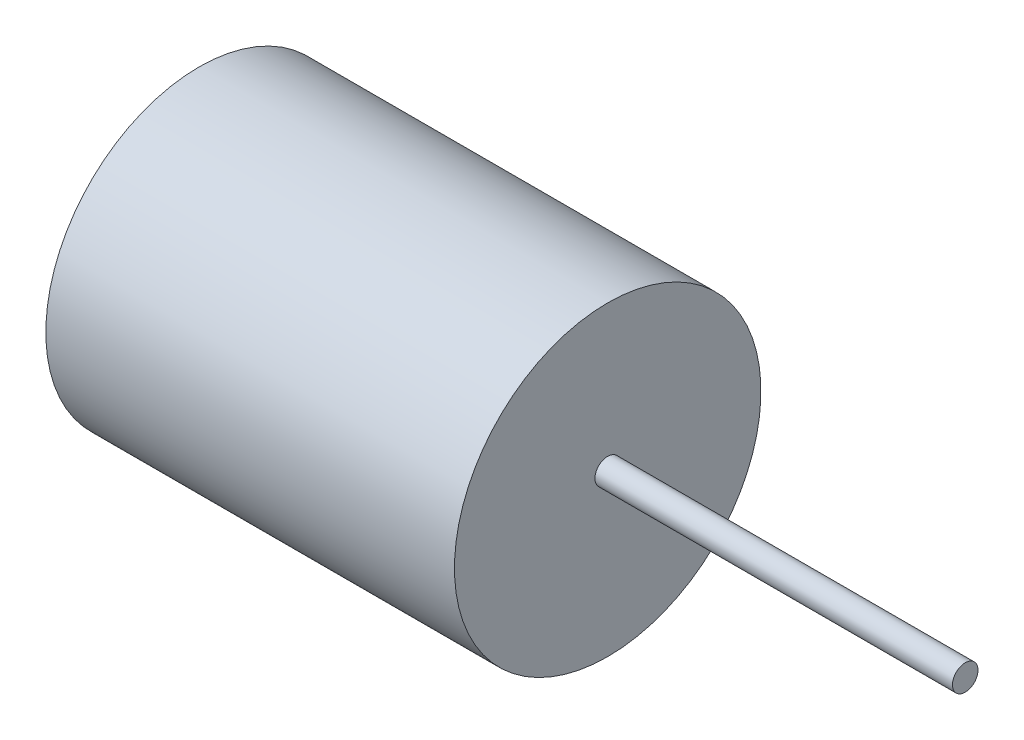
SolidWorks part; units mm, degrees
ref_plane "Front Plane" through (0, 0, 0) normal (0, 0, 1) x (1, 0, 0)
ref_plane "Top Plane" through (0, 0, 0) normal (0, 1, 0) x (1, 0, 0)
ref_plane "Right Plane" through (0, 0, 0) normal (1, 0, 0) x (0, 0, -1)
sketch "Sketch2" plane through (0, 0, 0) normal (0, 0, 1) x (1, 0, 0)
  line L0 (-48.5162, 28.5227) -> (31.4838, 28.5227)
  line L1 (31.4838, 28.5227) -> (31.4838, -1.4773)
  line L2 (31.4838, -1.4773) -> (-48.5162, -1.4773)
  line L3 (-48.5162, -1.4773) -> (-48.5162, 28.5227)
  dimension "D1" = 30
  dimension "D2" = 30
  dimension "D3" = 80
revolve "Revolve1" add sketch "Sketch2" angle 360 about L2
ref_plane "Plane1" through (31.4838, 0, 0) normal (1, 0, 0) x (0, 0, -1)
sketch "Sketch3" plane through (31.4838, 0, 0) normal (1, 0, 0) x (0, 0, -1)
  circle A0 centre (0, 0) radius 2.5
  dimension "D1" = 5
extrude "Boss-Extrude1" add sketch "Sketch3" along normal blind 70
